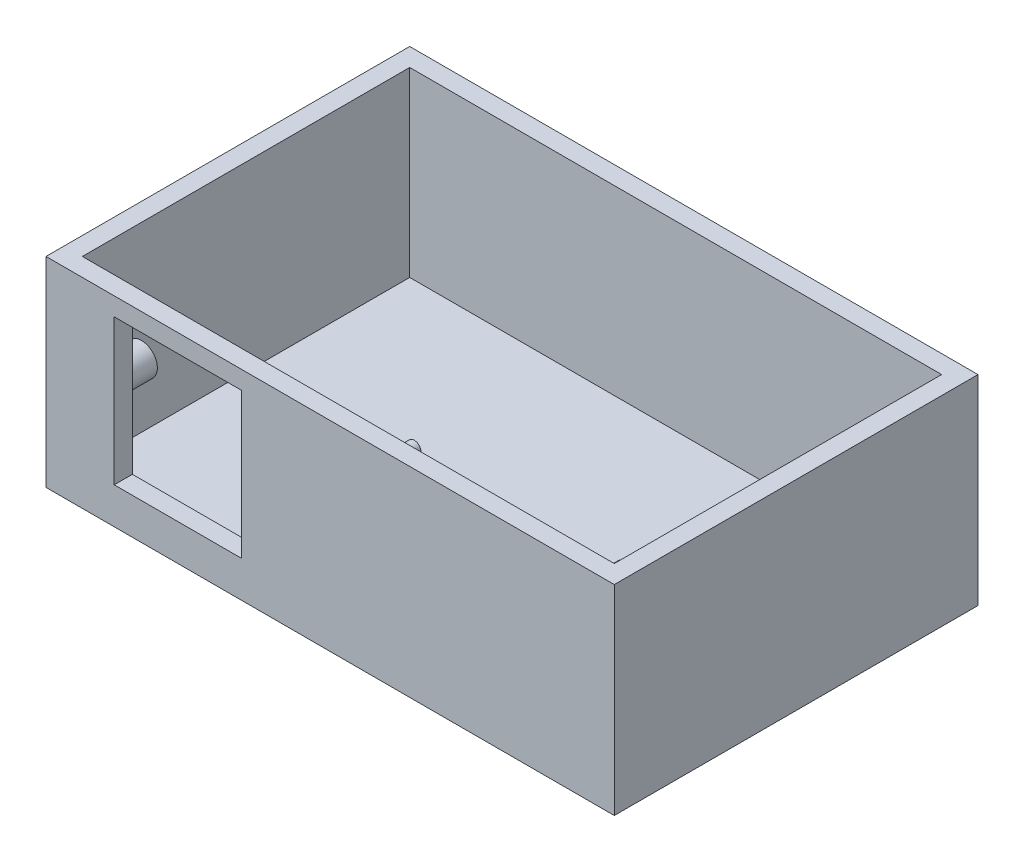
SolidWorks part; units mm, degrees
ref_plane "Front Plane" through (0, 0, 0) normal (0, 0, 1) x (1, 0, 0)
ref_plane "Top Plane" through (0, 0, 0) normal (0, 1, 0) x (1, 0, 0)
ref_plane "Right Plane" through (0, 0, 0) normal (1, 0, 0) x (0, 0, -1)
sketch "base sketch" plane through (0, 0, 0) normal (0, 1, 0) x (1, 0, 0)
  line L1 (0, 0) -> (125, 0)
  line L2 (0, 0) -> (0, 80)
  line L3 (0, 80) -> (125, 80)
  line L4 (125, 0) -> (125, 80)
  dimension "D1" = 125
  dimension "D2" = 80
extrude "base extrude" add sketch "base sketch" along normal blind 4
ref_plane "wall base plane" through (0, 4, 0) normal (0, 1, 0) x (1, 0, 0)
sketch "wall base sketch" plane through (0, 4, 0) normal (0, 1, 0) x (1, 0, 0)
  line L0 (4, 76) -> (121, 76)
  line L1 (0, 80) -> (125, 80)
  line L2 (0, 80) -> (0, 0)
  line L3 (0, 0) -> (125, 0)
  line L4 (125, 80) -> (125, 0)
  line L5 (121, 76) -> (121, 4)
  line L6 (4, 4) -> (121, 4)
  line L7 (4, 76) -> (4, 4)
  dimension "D1" = 4
extrude "wall base extrude" add sketch "wall base sketch" along normal blind 40
ref_plane "right wall plane" through (0, 0, 0) normal (0, 0, 1) x (1, 0, 0)
sketch "speaker hole sketch" plane through (0, 0, 0) normal (0, 0, 1) x (1, 0, 0)
  line L0 (0, 44) -> (125, 44) construction
  line L1 (15, 8) -> (43, 8)
  line L2 (15, 8) -> (15, 40)
  line L3 (15, 40) -> (43, 40)
  line L4 (43, 8) -> (43, 40)
  line L5 (0, 44) -> (0, 0) construction
  dimension "D1" = 28
  dimension "D2" = 32
  dimension "D3" = 4
  dimension "D4" = 15
extrude "speaker hole" cut sketch "speaker hole sketch" against normal blind 7
ref_plane "speaker standoffs" through (0, 0, -4) normal (0, 0, -1) x (-1, 0, 0)
sketch "speaker standoffs sketch" plane through (0, 0, -4) normal (0, 0, -1) x (-1, 0, 0)
  line L0 (-43, 40) -> (-43, 8) construction
  line L1 (-4, 44) -> (-121, 44) construction
  line L2 (-15, 8) -> (-15, 40) construction
  line L3 (-121, 44) -> (-121, 4) construction
  circle A0 centre (-48, 24) radius 3.5
  circle A1 centre (-10, 24) radius 3.5
  circle A2 centre (-116, 37) radius 1.5
  circle A3 centre (-70, 37) radius 1.5
  circle A4 centre (-116, 13.5) radius 1.5
  circle A5 centre (-70, 14) radius 1.5
  point P11 (-48, 24)
  point P12 (-10, 24)
  point P13 (-48, 24)
  dimension "D2" = 7
  dimension "D3" = 7
  dimension "D4" = 20
  dimension "D5" = 20
  dimension "D6" = 5
  dimension "D7" = 3
  dimension "D8" = 5
  dimension "D9" = 3
  dimension "D10" = 5
  dimension "D11" = 7
  dimension "D12" = 23.5
  dimension "D13" = 46
  dimension "D14" = 3
  dimension "D15" = 7
  dimension "D16" = 3
  dimension "D17" = 23
  dimension "D18" = 46
  dimension "D1" = 5
extrude "speaker standoffs extrude" add sketch "speaker standoffs sketch" along normal blind 7
hole_wizard "M1.2x0.25 Tapped Hole2" positions "3DSketch4" profile "Sketch9" tap size "M1.2x0.25" standard "ANSI Metric"
sketch3d "3DSketch4"
  line L0 (116, 13.5, -11) -> (116, 13.5, -4) construction
  line L1 (116, 37, -11) -> (116, 37, -4) construction
  circle A0 centre (48, 24, -11) radius 3.5 construction
  circle A1 centre (10, 24, -11) radius 3.5 construction
  circle A2 centre (70, 37, -11) radius 1.5 construction
  circle A3 centre (70, 14, -11) radius 1.5 construction
  point P0 (48, 24, -11)
  point P2 (10, 24, -11)
  point P5 (48, 24, -14.5)
  point P8 (10, 24, -14.5)
  point P9 (70, 14, -11)
  point P11 (70, 37, -11)
  point P13 (116, 13.5, -11)
  point P17 (116, 37, -11)
  point P24 (70, 37, -12.5)
  point P27 (70, 14, -12.5)
  dimension "D1" = 0
  dimension "D2" = 0
  dimension "D3" = 0
  dimension "D4" = 0
sketch "Sketch9" plane through (48, 24, -11) normal (1, 0, 0) x (0, 1, 0)
  line L0 (0, 0) -> (0, 3.4354)
  line L1 (0, 3.4354) -> (0.475, 3.15)
  line L2 (0.475, 3.15) -> (0.475, 0)
  line L5 (0.475, 0) -> (0, 0)
  line L10 (0, 3.4354) -> (-0.475, 3.15) construction
  line L11 (0, -6.35) -> (0, 107.95) construction
  dimension "Tap Drill Dia." = 0.95
  dimension "Tap Drill Depth" = 3.15
  dimension "Drill Angle" = 118
cosmetic thread "Hole Thread1" parameters "D1"=2.4, "D2"=1.2
cosmetic thread "Hole Thread2" parameters "D1"=2.4, "D2"=1.2
cosmetic thread "Hole Thread3" parameters "D1"=2.4, "D2"=1.2
cosmetic thread "Hole Thread4" parameters "D1"=2.4, "D2"=1.2
cosmetic thread "Hole Thread5" parameters "D1"=2.4, "D2"=1.2
cosmetic thread "Hole Thread6" parameters "D1"=2.4, "D2"=1.2
